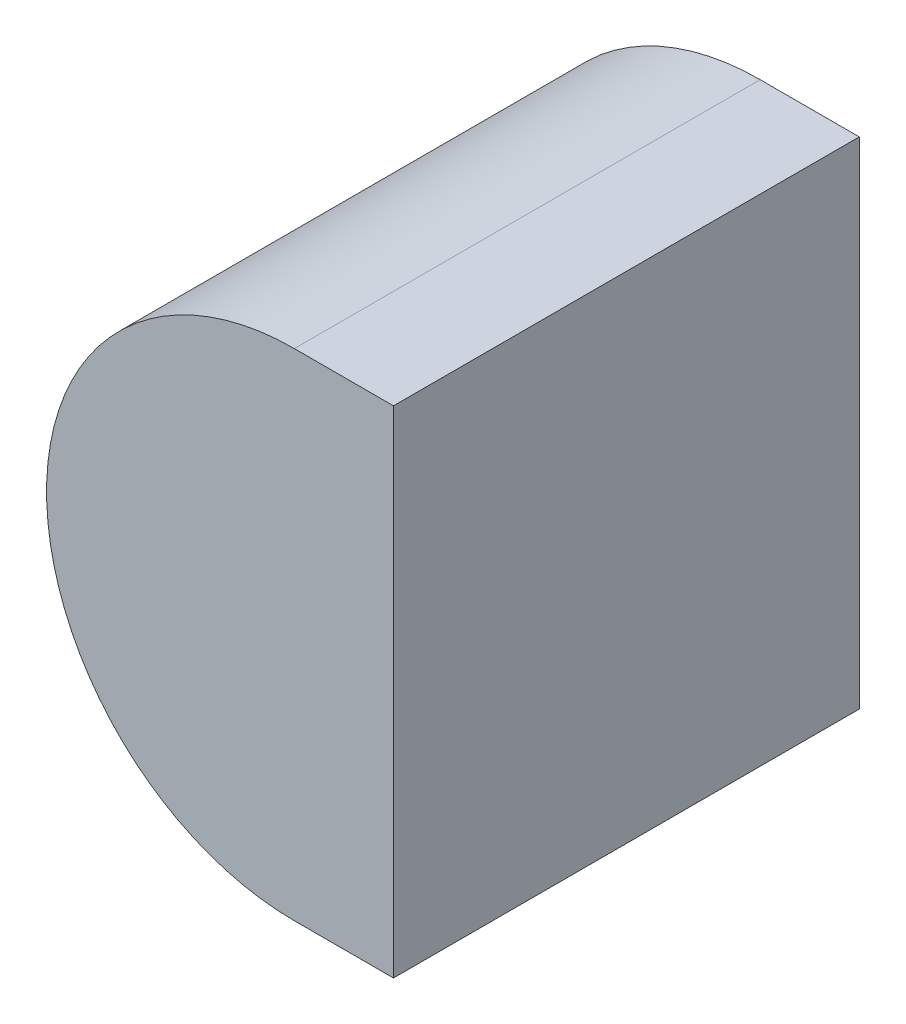
SolidWorks part; units mm, degrees
ref_plane "Front Plane" through (0, 0, 0) normal (0, 0, 1) x (1, 0, 0)
ref_plane "Top Plane" through (0, 0, 0) normal (0, 1, 0) x (1, 0, 0)
ref_plane "Right Plane" through (0, 0, 0) normal (1, 0, 0) x (0, 0, -1)
sketch "Sketch1" plane through (0, 0, 0) normal (0, 0, 1) x (1, 0, 0)
  line L1 (458.4617, 7.2013) -> (457.4617, 7.2013)
  line L2 (458.4617, 7.2013) -> (458.4617, 2.2013)
  line L3 (458.4617, 2.2013) -> (457.4617, 2.2013)
  line L4 (457.4617, 7.2013) -> (457.4617, 2.2013) construction
  line L5 (458.4617, 7.2013) -> (457.4617, 2.2013) construction
  line L6 (458.4617, 2.2013) -> (457.4617, 7.2013) construction
  arc A0 (457.4617, 7.2013) -> (457.4617, 2.2013) centre (457.4617, 4.7013) ccw
  point P3 (457.9617, 4.7013)
  point P9 (457.4617, 4.7013)
  dimension "D1" = 2.5
  dimension "D2" = 1
extrude "Boss-Extrude1" add sketch "Sketch1" along normal blind 4.7
